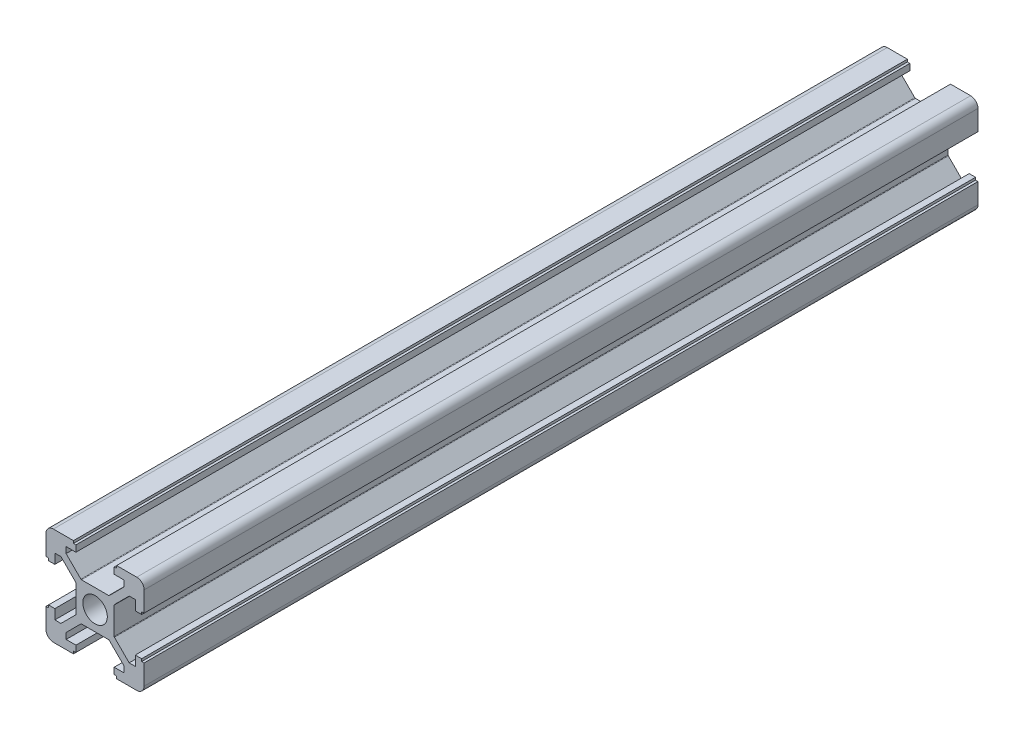
SolidWorks part; units mm, degrees
ref_plane "前视基准面" through (0, 0, 0) normal (0, 0, 1) x (1, 0, 0)
ref_plane "上视基准面" through (0, 0, 0) normal (0, 1, 0) x (1, 0, 0)
ref_plane "右视基准面" through (0, 0, 0) normal (1, 0, 0) x (0, 0, -1)
other "Configuration Table"
sketch "草图1" plane through (0, 0, 0) normal (0, 0, 1) x (1, 0, 0)
  line L0 (-10, 0) -> (10, 0) construction
  line L1 (-10, 10) -> (-4.4, 10)
  line L2 (-10, 10) -> (-10, 4.4)
  line L3 (-10, -10) -> (-4.4, -10)
  line L4 (10, 10) -> (10, 4.4)
  line L5 (-10, 10) -> (10, -10) construction
  line L6 (-10, -10) -> (10, 10) construction
  line L7 (-2.8396, 3.9001) -> (2.8395, 3.9001)
  line L8 (-3.9, 2.8393) -> (-3.9, -2.8395)
  line L9 (-2.8393, -3.9) -> (2.8395, -3.9)
  line L10 (3.9001, 2.8396) -> (3.9001, -2.8395)
  line L11 (-3.9, 3.9) -> (3.9, -3.9) construction
  line L12 (-3.9, -3.9) -> (3.9, 3.9) construction
  line L13 (0, 10) -> (0, -10) construction
  line L14 (-6.9607, 5.9) -> (-3.9, 2.8393)
  line L15 (-5.9, 6.9607) -> (-2.8396, 3.9001)
  line L16 (-6.9607, 5.9) -> (-8.2, 5.9)
  line L17 (-8.2, 5.9) -> (-8.2, 3.9)
  line L18 (-8.2, 3.9) -> (-9.5, 3.9)
  line L19 (-9.5, 3.9) -> (-9.5, 4.4)
  line L20 (-9.5, 4.4) -> (-10, 4.4)
  line L21 (-5.9, 6.9607) -> (-5.9, 8.2)
  line L22 (-5.9, 8.2) -> (-3.9, 8.2)
  line L23 (-3.9, 8.2) -> (-3.9, 9.5)
  line L24 (-3.9, 9.5) -> (-4.4, 9.5)
  line L25 (-4.4, 9.5) -> (-4.4, 10)
  line L26 (6.9607, 5.9) -> (3.9001, 2.8396)
  line L27 (5.9, 6.9607) -> (2.8393, 3.9)
  line L28 (5.9, 6.9607) -> (5.9, 8.2)
  line L29 (5.9, 8.2) -> (3.9, 8.2)
  line L30 (3.9, 8.2) -> (3.9, 9.5)
  line L31 (3.9, 9.5) -> (4.4, 9.5)
  line L32 (4.4, 9.5) -> (4.4, 10)
  line L33 (6.9607, 5.9) -> (8.2, 5.9)
  line L34 (8.2, 5.9) -> (8.2, 3.9)
  line L35 (8.2, 3.9) -> (9.5, 3.9)
  line L36 (9.5, 3.9) -> (9.5, 4.4)
  line L37 (9.5, 4.4) -> (10, 4.4)
  line L38 (5.9, -6.9607) -> (2.8395, -3.9)
  line L39 (6.9607, -5.9) -> (3.9, -2.8393)
  line L40 (6.9607, -5.9) -> (8.2, -5.9)
  line L41 (8.2, -5.9) -> (8.2, -3.9)
  line L42 (8.2, -3.9) -> (9.5, -3.9)
  line L43 (9.5, -3.9) -> (9.5, -4.4)
  line L44 (9.5, -4.4) -> (10, -4.4)
  line L45 (5.9, -6.9607) -> (5.9, -8.2)
  line L46 (5.9, -8.2) -> (3.9, -8.2)
  line L47 (3.9, -8.2) -> (3.9, -9.5)
  line L48 (3.9, -9.5) -> (4.4, -9.5)
  line L49 (4.4, -9.5) -> (4.4, -10)
  line L50 (-6.9607, -5.9) -> (-3.9, -2.8395)
  line L51 (-5.9, -6.9607) -> (-2.8393, -3.9)
  line L52 (-5.9, -6.9607) -> (-5.9, -8.2)
  line L53 (-5.9, -8.2) -> (-3.9, -8.2)
  line L54 (-3.9, -8.2) -> (-3.9, -9.5)
  line L55 (-3.9, -9.5) -> (-4.4, -9.5)
  line L56 (-4.4, -9.5) -> (-4.4, -10)
  line L57 (-6.9607, -5.9) -> (-8.2, -5.9)
  line L58 (-8.2, -5.9) -> (-8.2, -3.9)
  line L59 (-8.2, -3.9) -> (-9.5, -3.9)
  line L60 (-9.5, -3.9) -> (-9.5, -4.4)
  line L61 (-9.5, -4.4) -> (-10, -4.4)
  line L62 (4.4, -10) -> (10, -10)
  line L63 (-10, -4.4) -> (-10, -10)
  line L64 (10, -10) -> (10, -4.4)
  line L65 (4.4, 10) -> (10, 10)
  circle A0 centre (0, 0) radius 2.5
  point P0 (0, 0)
  point P6 (0, 0)
  point P76 (0, 0)
  dimension "D6" = 5
  dimension "D1" = 20
  dimension "D2" = 20
  dimension "D3" = 7.8
  dimension "D4" = 7.8
  dimension "D5" = 0.75
  dimension "D7" = 0.5
  dimension "D8" = 0.5
  dimension "D9" = 1.8
  dimension "D10" = 6.1
  dimension "D12" = 2
  dimension "D11" = 4
extrude "凸台-拉伸1" add sketch "草图1" along normal blind 170
fillet "圆角1" radius 1.5 4 edges at (10, -10, 85) (-10, -10, 85) (-10, 10, 85) (10, 10, 85)
fillet "圆角2" radius 0.2 8 edges at (3.9001, -2.8395, 85) (3.9001, 2.8396, 85) (-2.8393, -3.9, 85) (2.8395, -3.9, 85) (-2.8396, 3.9001, 85) (2.8395, 3.9001, 85) (-3.9, 2.8393, 85) (-3.9, -2.8395, 85)
